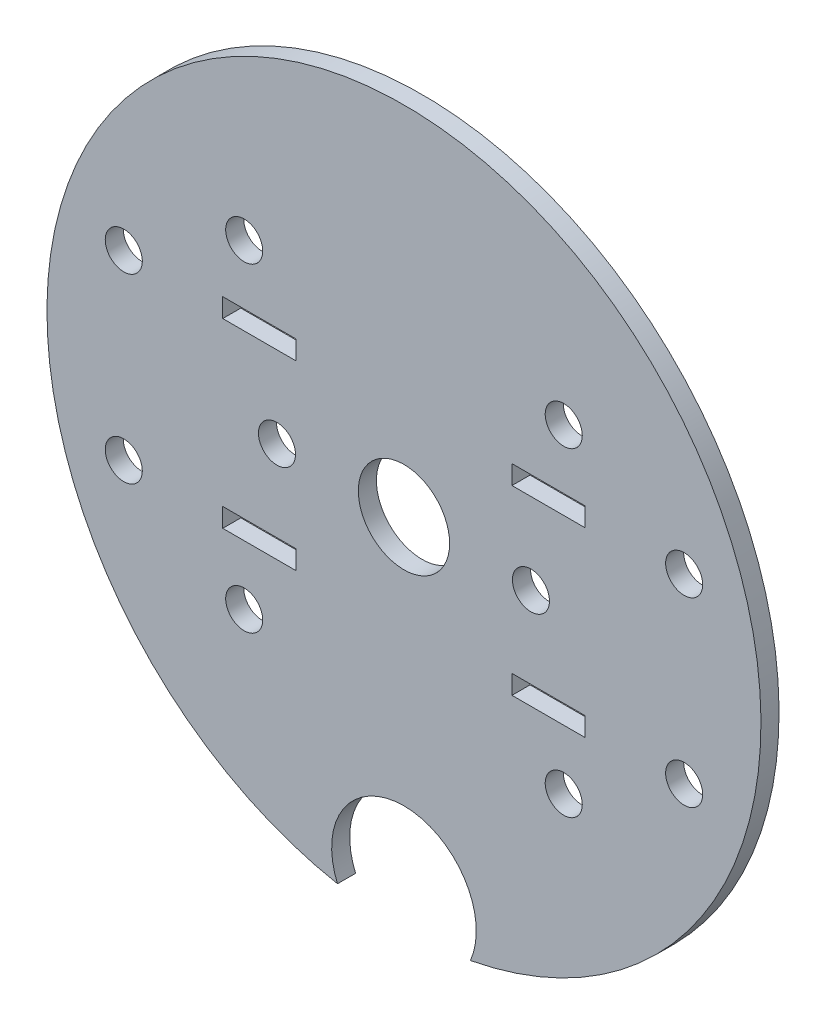
SolidWorks part; units mm, degrees
ref_plane "前视基准面" through (0, 0, 0) normal (0, 0, 1) x (1, 0, 0)
ref_plane "上视基准面" through (0, 0, 0) normal (0, 1, 0) x (1, 0, 0)
ref_plane "右视基准面" through (0, 0, 0) normal (1, 0, 0) x (0, 0, -1)
sketch "草图1" plane through (0, 0, 0) normal (0, 0, 1) x (1, 0, 0)
  line L0 (0, 0) -> (0, -39.5) construction
  line L1 (0, 0) -> (-16.3098, -16.3098) construction
  line L2 (0, 0) -> (16, 0) construction
  line L3 (16, 0) -> (16, 10.05) construction
  line L4 (20.05, -11.1) -> (20.05, -9)
  line L5 (11.95, 11.1) -> (20.05, 11.1)
  line L6 (11.95, 11.1) -> (11.95, 9)
  line L7 (11.95, 9) -> (20.05, 9)
  line L8 (20.05, 11.1) -> (20.05, 9)
  line L9 (11.95, 11.1) -> (20.05, 9) construction
  line L10 (11.95, 9) -> (20.05, 11.1) construction
  line L11 (11.95, -9) -> (20.05, -9)
  line L12 (11.95, -11.1) -> (11.95, -9)
  line L13 (11.95, -11.1) -> (20.05, -11.1)
  line L14 (-20.05, 11.1) -> (-20.05, 9)
  line L15 (-11.95, 11.1) -> (-11.95, 9)
  line L16 (-11.95, 11.1) -> (-20.05, 11.1)
  line L17 (-11.95, 9) -> (-20.05, 9)
  line L18 (-11.95, -11.1) -> (-11.95, -9)
  line L19 (-11.95, -9) -> (-20.05, -9)
  line L20 (-20.05, -11.1) -> (-20.05, -9)
  line L21 (-11.95, -11.1) -> (-20.05, -11.1)
  line L22 (16, 10.05) -> (31, 10.05) construction
  line L23 (0, 0) -> (-14.05, 0) construction
  circle A0 centre (0, 0) radius 5.05
  circle A1 centre (0, 0) radius 39.5 construction
  circle A2 centre (0, 0) radius 25 construction
  circle A3 centre (-17.6777, -17.6777) radius 2.05
  circle A4 centre (-17.6777, 17.6777) radius 2.05
  circle A5 centre (17.6777, 17.6777) radius 2.05
  circle A6 centre (17.6777, -17.6777) radius 2.05
  arc A9 (-7.355, -38.8092) -> (7.355, -38.8092) centre (0, 0) cw
  circle A10 centre (0, 0) radius 12 construction
  arc A11 (-7.355, -38.8092) -> (7.355, -38.8092) centre (0, -35.6621) cw
  circle A12 centre (31, 10.05) radius 2.05
  circle A13 centre (31, -10.05) radius 2.05
  circle A14 centre (-31, -10.05) radius 2.05
  circle A15 centre (-31, 10.05) radius 2.05
  circle A20 centre (-14.05, 0) radius 2.05
  circle A21 centre (14.05, 0) radius 2.05
  circle A22 centre (-14.05, 0) radius 1.15 construction
  circle A23 centre (14.05, 0) radius 1.15 construction
  dimension "D1" = 10.1
  dimension "D2" = 79
  dimension "D4" = 50
  dimension "D5" = 4
  dimension "D6" = 24
  dimension "D11" = 4.1
  dimension "D12" = 18
  dimension "D13" = 4.1
  dimension "D3" = 45
  dimension "D7" = 8.1
  dimension "D8" = 16
  dimension "D9" = 2.1
  dimension "D10" = 15
extrude "凸台-拉伸1" add sketch "草图1" along normal blind 2
